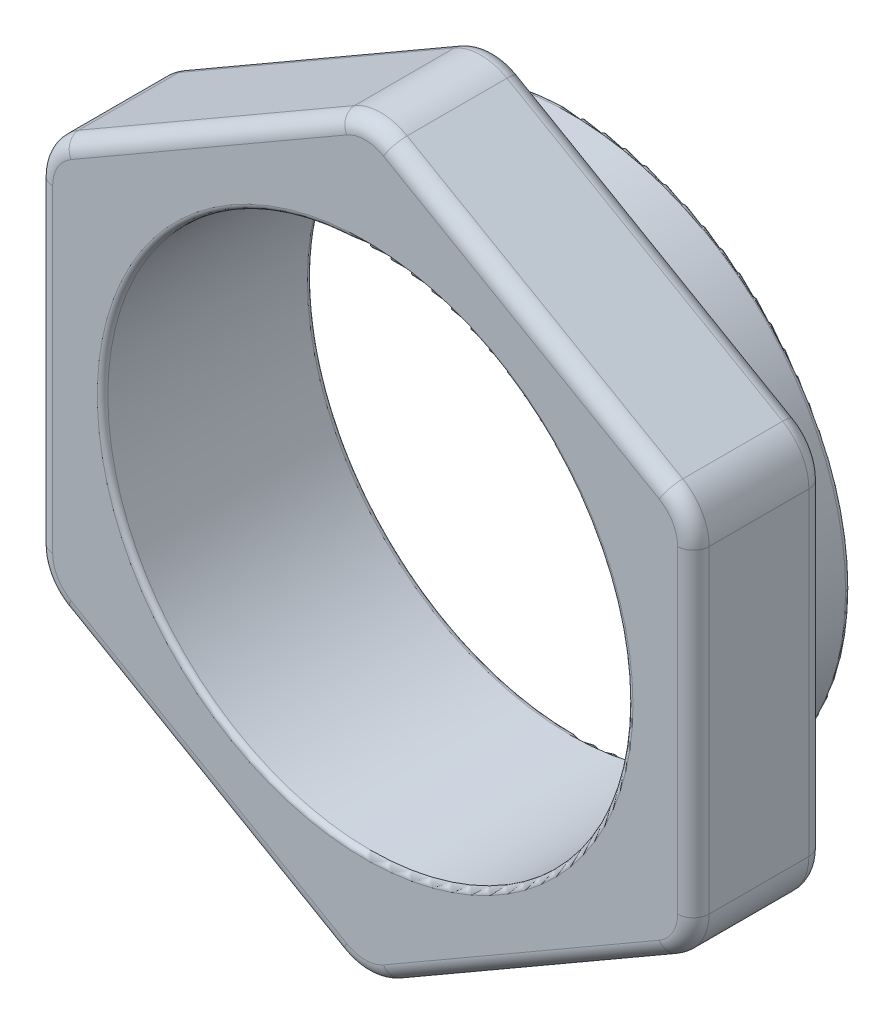
SolidWorks part; units mm, degrees
ref_plane "Front" through (0, 0, 0) normal (0, 0, 1) x (1, 0, 0)
ref_plane "Top" through (0, 0, 0) normal (0, 1, 0) x (1, 0, 0)
ref_plane "Right" through (0, 0, 0) normal (1, 0, 0) x (0, 0, -1)
sketch "Sketch1" plane through (0, 0, 0) normal (0, 0, 1) x (1, 0, 0)
  circle A0 centre (0, 0) radius 6.6675
  dimension "D1" = 13.335
extrude "Boss-Extrude1" add sketch "Sketch1" along normal blind 1.905
sketch "Sketch2" plane through (0, 0, 1.905) normal (0, 0, 1) x (1, 0, 0)
  line L1 (7.9375, 4.5827) -> (0, 9.1654)
  line L2 (0, 9.1654) -> (-7.9375, 4.5827)
  line L3 (-7.9375, 4.5827) -> (-7.9375, -4.5827)
  line L4 (-7.9375, -4.5827) -> (0, -9.1654)
  line L5 (0, -9.1654) -> (7.9375, -4.5827)
  line L6 (7.9375, -4.5827) -> (7.9375, 4.5827)
  circle A0 centre (0, 0) radius 7.9375 construction
  dimension "D1" = 15.875
extrude "Boss-Extrude2" add sketch "Sketch2" along normal blind 3.175 contours L2 L3 L4 L5 L6 L1
sketch "Sketch3" plane through (0, 0, 0) normal (0, 0, -1) x (-1, 0, 0)
  circle A0 centre (0, 0) radius 6.35
  dimension "D1" = 12.7
extrude "Cut-Extrude1" cut sketch "Sketch3" against normal through all
fillet "Fillet1" radius 1.27 6 edges at (7.9375, 4.5827, 3.4925) (7.9375, -4.5827, 3.4925) (0, -9.1654, 3.4925) (-7.9375, -4.5827, 3.4925) (-7.9375, 4.5827, 3.4925) (0, 9.1654, 3.4925)
fillet "Fillet2" radius 0.381 24 edges at (7.7674, 4.4845, 5.08) (7.9375, 0, 5.08) (7.7674, -4.4845, 5.08) (3.9688, -6.8741, 5.08) (0, -8.969, 5.08) (-3.9687, -6.8741, 5.08) (-7.7674, -4.4845, 5.08) (-7.9375, 0, 5.08) (-7.7674, 4.4845, 5.08) (-3.9687, 6.8741, 5.08) (0, 8.969, 5.08) (7.7674, 4.4845, 1.905) (7.9375, 0, 1.905) (7.7674, -4.4845, 1.905) (3.9688, -6.8741, 1.905) (0, -8.969, 1.905) (-3.9687, -6.8741, 1.905) (-7.7674, -4.4845, 1.905) (-7.9375, 0, 1.905) (-7.7674, 4.4845, 1.905) (-3.9687, 6.8741, 1.905) (0, 8.969, 1.905) (3.9688, 6.8741, 5.08) (3.9688, 6.8741, 1.905)
fillet "Fillet3" radius 0.127 3 edges at (6.6675, 0, 0) (-6.35, 0, 0) (-6.35, 0, 5.08)
